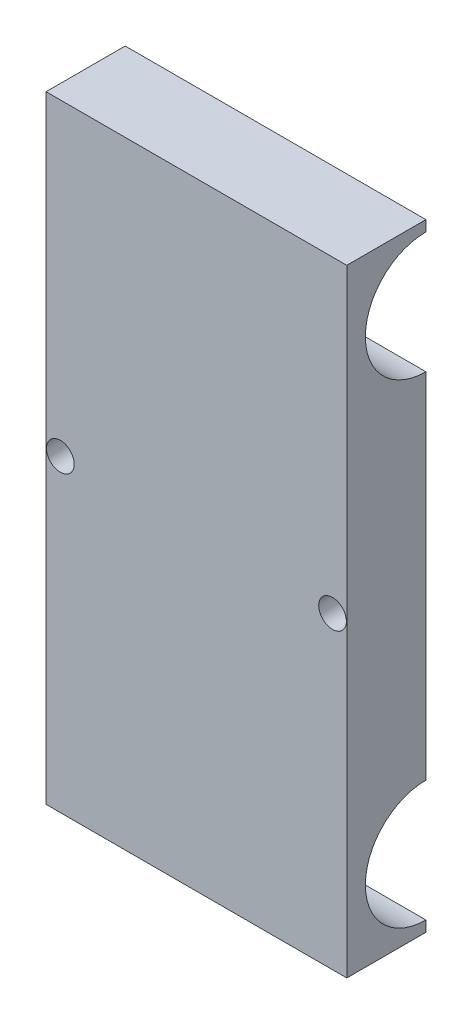
SolidWorks part; units mm, degrees
ref_plane "Front Plane" through (0, 0, 0) normal (0, 0, 1) x (1, 0, 0)
ref_plane "Top Plane" through (0, 0, 0) normal (0, 1, 0) x (1, 0, 0)
ref_plane "Right Plane" through (0, 0, 0) normal (1, 0, 0) x (0, 0, -1)
sketch "Sketch1" plane through (0, 0, 0) normal (0, 0, 1) x (1, 0, 0)
  line L1 (0, 0) -> (38, 0)
  line L2 (0, 0) -> (0, 78)
  line L3 (0, 78) -> (38, 78)
  line L4 (38, 0) -> (38, 78)
  dimension "D1" = 78
  dimension "D2" = 38
extrude "Boss-Extrude1" add sketch "Sketch1" along normal blind 10
sketch "Sketch2" plane through (0, 0, 0) normal (-1, 0, 0) x (0, 0, 1)
  line L0 (0, 78) -> (0, 0) construction
  line L1 (10, 0) -> (0, 0) construction
  circle A0 centre (0, 69) radius 7.65
  circle A1 centre (0, 9) radius 7.65
  dimension "D2" = 15.3
  dimension "D3" = 60
  dimension "D4" = 9
extrude "Cut-Extrude1" cut sketch "Sketch2" against normal through all
sketch "Sketch3" plane through (0, 0, 0) normal (0, 0, -1) x (-1, 0, 0)
  line L0 (-38, 39) -> (0, 39) construction
  line L1 (-38, 16.65) -> (-38, 61.35) construction
  line L2 (0, 61.35) -> (0, 16.65) construction
  circle A0 centre (-36.2, 39) radius 1.75
  circle A1 centre (-1.8, 39) radius 1.75
  dimension "D1" = 3.5
  dimension "D2" = 1.8
  dimension "D3" = 1.8
extrude "Cut-Extrude2" cut sketch "Sketch3" against normal through all
